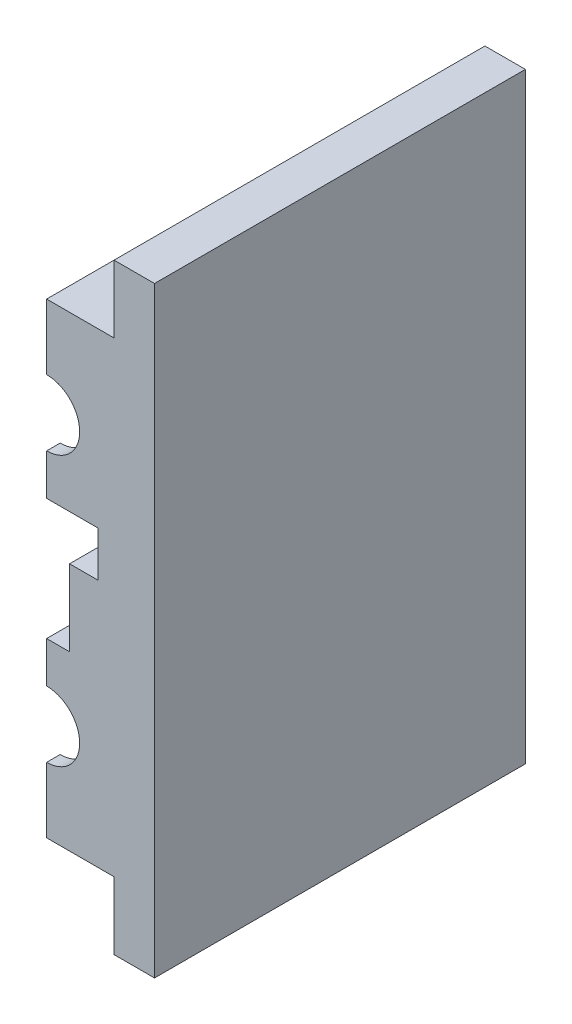
SolidWorks part; units mm, degrees
ref_plane "Front Plane" through (0, 0, 0) normal (0, 0, 1) x (1, 0, 0)
ref_plane "Top Plane" through (0, 0, 0) normal (0, 1, 0) x (1, 0, 0)
ref_plane "Right Plane" through (0, 0, 0) normal (1, 0, 0) x (0, 0, -1)
sketch "Sketch1" plane through (0, 0, 0) normal (0, 0, 1) x (1, 0, 0)
  line L0 (0, 0) -> (0, -89.2)
  line L1 (0, -89.2) -> (-6, -89.2)
  line L2 (-6, -89.2) -> (-6, -79.2)
  line L3 (-6, -79.2) -> (-16, -79.2)
  line L4 (-16, -79.2) -> (-16, -72.2)
  line L5 (-16, -57) -> (-16, -42.3)
  line L6 (-16, -42.3) -> (-8.4, -42.3)
  line L7 (-8.4, -42.3) -> (-8.4, -35.6)
  line L8 (-8.4, -35.6) -> (-16, -35.6)
  line L9 (-16, -35.6) -> (-16, -32.2)
  line L10 (-16, -17) -> (-16, -10)
  line L11 (-16, -10) -> (-6, -10)
  line L12 (-6, -10) -> (-6, 0)
  line L13 (-6, 0) -> (0, 0)
  arc A0 (-16, -72.2) -> (-16, -57) centre (-16, -64.6) ccw
  arc A1 (-16, -32.2) -> (-16, -17) centre (-16, -24.6) ccw
  dimension "D6" = 7.6
  dimension "D7" = 7.6
  dimension "D1" = 6
  dimension "D2" = 10
  dimension "D3" = 10
  dimension "D4" = 14.7
  dimension "D5" = 40
  dimension "D8" = 7
  dimension "D9" = 3.4
  dimension "D11" = 10
  dimension "D12" = 10
extrude "Boss-Extrude1" add sketch "Sketch1" along normal blind 55
ref_plane "Plane1" through (0, 0, 28.5) normal (0, 0, -1) x (-1, 0, 0)
sketch "Sketch2" plane through (0, 0, 28.5) normal (0, 0, -1) x (-1, 0, 0)
  line L0 (16, -32.2) -> (16, -29.5)
  line L1 (16, -19.7) -> (16, -17)
  arc A0 (16, -17) -> (16, -32.2) centre (16, -24.6) ccw
  arc A1 (16, -19.7) -> (16, -29.5) centre (16, -24.6) ccw
  dimension "D1" = 4.9
extrude "Boss-Extrude2" add sketch "Sketch2" along normal blind 2
sketch "Sketch3" plane through (0, 0, 28.5) normal (0, 0, -1) x (-1, 0, 0)
  line L0 (16, -72.2) -> (16, -69.5)
  line L1 (16, -59.7) -> (16, -57)
  arc A0 (16, -57) -> (16, -72.2) centre (16, -64.6) ccw
  arc A1 (16, -59.7) -> (16, -69.5) centre (16, -64.6) ccw
  dimension "D1" = 4.9
extrude "Boss-Extrude3" add sketch "Sketch3" along normal blind 2
ref_plane "Plane2" through (0, 0, 2) normal (0, 0, -1) x (-1, 0, 0)
sketch "Sketch4" plane through (0, 0, 2) normal (0, 0, -1) x (-1, 0, 0)
  line L1 (16, -57) -> (16, -59.7)
  line L2 (16, -72.2) -> (16, -79.2) construction
  line L4 (16, -69.5) -> (16, -72.2)
  line L5 (16, -17) -> (16, -19.7)
  line L6 (16, -29.5) -> (16, -32.2)
  arc A1 (16, -57) -> (16, -72.2) centre (16, -64.6) ccw construction
  arc A2 (16, -72.2) -> (16, -57) centre (16, -64.6) cw
  arc A4 (16, -59.7) -> (16, -69.5) centre (16, -64.6) ccw
  arc A5 (16, -32.2) -> (16, -17) centre (16, -24.6) cw
  arc A6 (16, -19.7) -> (16, -29.5) centre (16, -24.6) ccw
  dimension "D1" = 4.9
  dimension "D2" = 4.9
extrude "Boss-Extrude5" add sketch "Sketch4" along normal blind 2
ref_plane "Plane3" through (0, 0, 53) normal (0, 0, -1) x (-1, 0, 0)
sketch "Sketch5" plane through (0, 0, 53) normal (0, 0, -1) x (-1, 0, 0)
  line L0 (16, -17) -> (16, -19.7)
  line L1 (16, -29.5) -> (16, -32.2)
  line L2 (16, -57) -> (16, -59.7)
  line L3 (16, -69.5) -> (16, -72.2)
  arc A0 (16, -17) -> (16, -32.2) centre (16, -24.6) ccw construction
  arc A1 (16, -32.2) -> (16, -17) centre (16, -24.6) cw
  arc A2 (16, -19.7) -> (16, -29.5) centre (16, -24.6) ccw
  arc A3 (16, -72.2) -> (16, -57) centre (16, -64.6) cw
  arc A4 (16, -59.7) -> (16, -69.5) centre (16, -64.6) ccw
  dimension "D1" = 4.9
extrude "Boss-Extrude6" add sketch "Sketch5" against normal blind 2
sketch "Sketch7" plane through (0, 0, 55) normal (0, 0, 1) x (1, 0, 0)
  line L1 (-16, -42.3) -> (-12.6, -42.3)
  line L2 (-16, -42.3) -> (-16, -53.6)
  line L3 (-16, -53.6) -> (-12.6, -53.6)
  line L4 (-12.6, -42.3) -> (-12.6, -53.6)
  dimension "D1" = 3.4
  dimension "D2" = 11.3
extrude "Cut-Extrude2" cut sketch "Sketch7" against normal up to surface (55 mm away) up to face at (-9.9375, -43.1875, 0)
